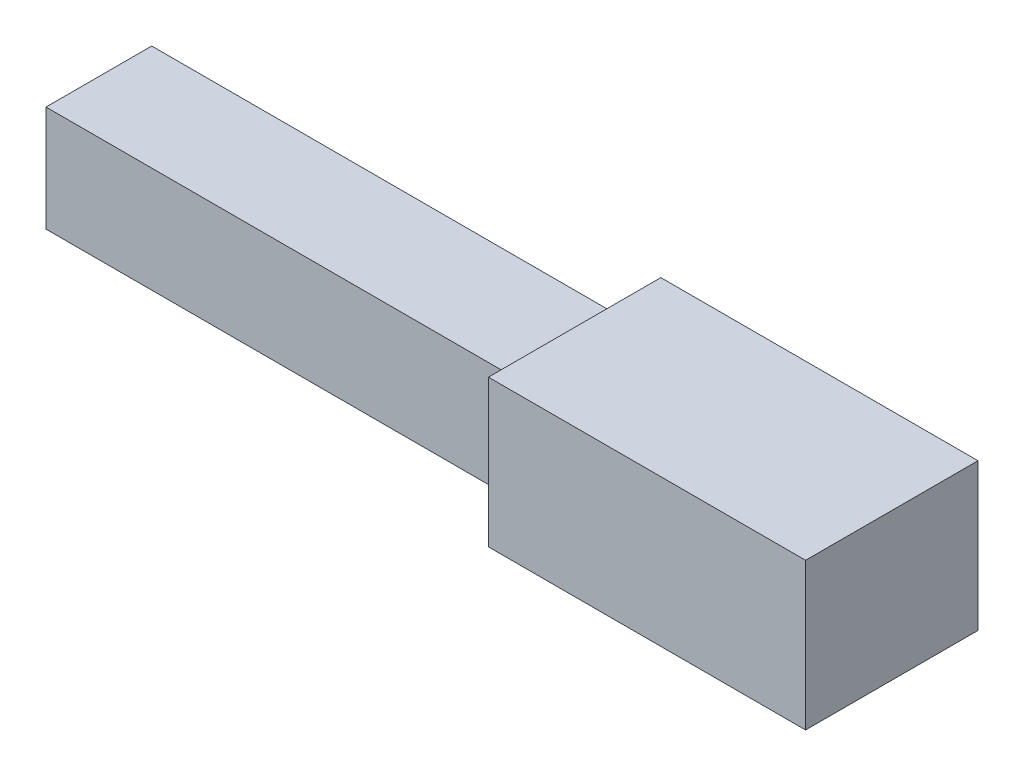
SolidWorks part; units mm, degrees
ref_plane "Alzado" through (0, 0, 0) normal (0, 0, 1) x (1, 0, 0)
ref_plane "Planta" through (0, 0, 0) normal (0, 1, 0) x (1, 0, 0)
ref_plane "Vista lateral" through (0, 0, 0) normal (1, 0, 0) x (0, 0, -1)
sketch "Croquis1" plane through (0, 0, 0) normal (1, 0, 0) x (0, 0, -1)
  line L1 (0, 0) -> (40, 0)
  line L2 (0, 0) -> (0, 40)
  line L3 (0, 40) -> (40, 40)
  line L4 (40, 0) -> (40, 40)
  dimension "D1" = 40
  dimension "D2" = 40
extrude "Saliente-Extruir1" add sketch "Croquis1" along normal blind 180
sketch "Croquis2" plane through (180, 0, 0) normal (1, 0, 0) x (0, 0, -1)
  line L1 (-12.6146, 47.8057) -> (52.6146, 47.8057)
  line L2 (-12.6146, 47.8057) -> (-12.6146, -7.8057)
  line L3 (-12.6146, -7.8057) -> (52.6146, -7.8057)
  line L4 (52.6146, 47.8057) -> (52.6146, -7.8057)
  line L5 (-12.6146, 47.8057) -> (52.6146, -7.8057) construction
  line L6 (-12.6146, -7.8057) -> (52.6146, 47.8057) construction
  point P0 (20, 20)
extrude "Saliente-Extruir2" add sketch "Croquis2" along normal blind 120
